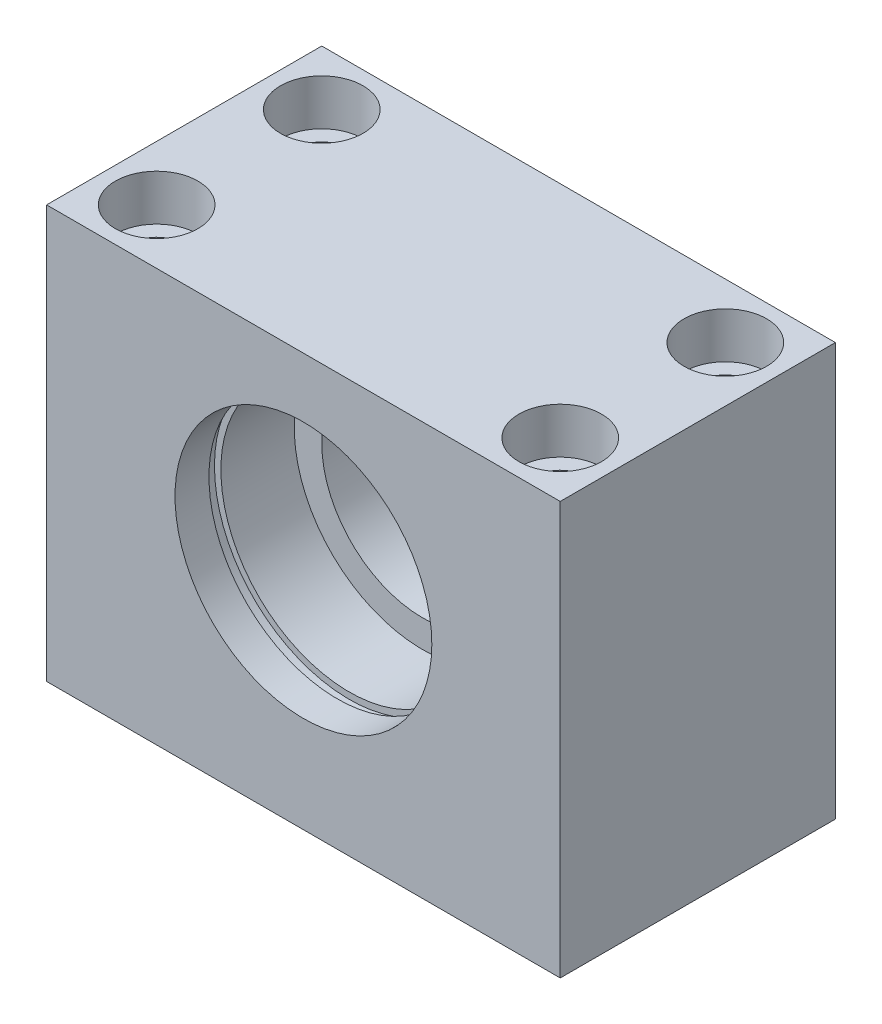
SolidWorks part; units mm, degrees
material "1.0037 (S235JR)"
ref_plane "Płaszczyzna przednia" through (0, 0, 0) normal (0, 0, 1) x (1, 0, 0)
ref_plane "Płaszczyzna górna" through (0, 0, 0) normal (0, 1, 0) x (1, 0, 0)
ref_plane "Płaszczyzna prawa" through (0, 0, 0) normal (1, 0, 0) x (0, 0, -1)
sketch "Szkic1" plane through (0, 0, 0) normal (0, 1, 0) x (1, 0, 0)
  line L1 (-28, -15) -> (28, -15)
  line L2 (-28, -15) -> (-28, 15)
  line L3 (-28, 15) -> (28, 15)
  line L4 (28, -15) -> (28, 15)
  line L5 (-28, -15) -> (28, 15) construction
  line L6 (-28, 15) -> (28, -15) construction
  point P0 (0, 0)
  dimension "D1" = 30
  dimension "D2" = 56
extrude "Dodanie-wyciągnięcie1" add sketch "Szkic1" along normal blind 45
sketch "Szkic3" plane through (0, 0, 15) normal (0, 0, 1) x (1, 0, 0)
  line L0 (0, 45) -> (0, 0) construction
  line L1 (-28, 45) -> (28, 45) construction
  line L2 (-28, 0) -> (28, 0) construction
  circle A0 centre (0, 24.5) radius 11
  dimension "D1" = 22
  dimension "D2" = 24.5
extrude "Wytnij-wyciągnięcie2" cut sketch "Szkic3" against normal through all
sketch "Szkic4" plane through (0, 0, 15) normal (0, 0, 1) x (1, 0, 0)
  circle A0 centre (0, 24.5) radius 14
  dimension "D1" = 28
extrude "Wytnij-wyciągnięcie3" cut sketch "Szkic4" against normal blind 13
sketch "Szkic5" plane through (0, 0, 0) normal (1, 0, 0) x (0, 0, -1)
  line L0 (-15, 10.5) -> (-2, 10.5) construction
  line L1 (-10, 10.5) -> (-11.3, 10.5)
  line L2 (-10, 10.5) -> (-10, 9.8)
  line L3 (-10, 9.8) -> (-11.3, 9.8)
  line L4 (-11.3, 10.5) -> (-11.3, 9.8)
  line L6 (-9.2946, 24.5) -> (-18.2923, 24.5) construction
  line L7 (-15, 38.5) -> (-15, 10.5) construction
  dimension "D1" = 1.3
  dimension "D2" = 14.7
  dimension "D3" = 5
  dimension "D4" = 24.5
sketch "Szkic6" plane through (0, 45, 0) normal (0, 1, 0) x (1, 0, 0)
  line L10 (22, -9) -> (22, 9)
  line L11 (22, 9) -> (-22, 9)
  line L12 (-22, 9) -> (-22, -9)
  line L13 (-22, -9) -> (22, -9)
  line L14 (22, -9) -> (22, 9)
  line L15 (22, 9) -> (-22, 9)
  line L16 (-22, 9) -> (-22, -9)
  line L17 (-22, -9) -> (22, -9)
  dimension "D1" = 6
hole_wizard "Pogłębienie walcowe pod M5 Wkręt do części metalowych z łbem sześciokątnym1" positions "Szkic8" profile "Szkic7" counterbore size "M5" standard "Ansi Metric" end condition through all
sketch "Szkic8" plane through (0, 45, 0) normal (0, 1, 0) x (1, 0, 0)
  point P0 (22, 9)
  point P3 (22, -9)
  point P6 (-22, -9)
  point P9 (-22, 9)
sketch "Szkic7" plane through (22, 45, -9) normal (1, 0, 0) x (0, 0, 1)
  line L0 (0, 0) -> (0, 45)
  line L1 (0, 45) -> (2.75, 45)
  line L3 (2.75, 45) -> (2.75, 5)
  line L4 (2.75, 5) -> (4.5, 5)
  line L5 (4.5, 5) -> (4.5, 0)
  line L7 (4.5, 0) -> (0, 0)
  line L11 (0, -6.35) -> (0, 107.95) construction
  dimension "Średnica otworu na wylot" = 5.5
  dimension "Głębokość otworu na wylot" = 45
  dimension "Średnica pogłębienia walcowego" = 9
  dimension "Głębokość pogłębienia walcowego" = 5
revolve "Wycięcie-obrót1" cut sketch "Szkic5" angle 360 about L6
